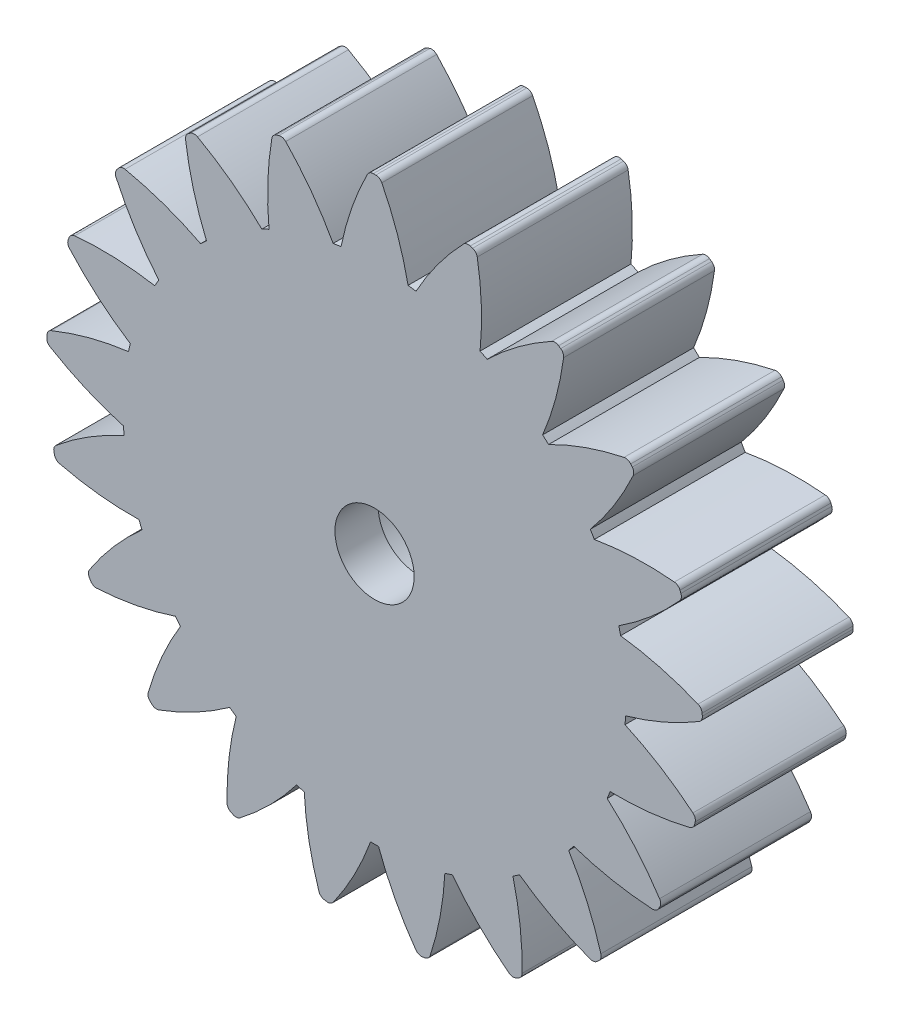
SolidWorks part; units mm, degrees
material "PET"
ref_plane "Front Plane" through (0, 0, 0) normal (0, 0, 1) x (1, 0, 0)
ref_plane "Top Plane" through (0, 0, 0) normal (0, 1, 0) x (1, 0, 0)
ref_plane "Right Plane" through (0, 0, 0) normal (1, 0, 0) x (0, 0, -1)
sketch "Sketch2" plane through (0, 0, 0) normal (0, 0, 1) x (1, 0, 0)
  circle A0 centre (0, 0) radius 9.525
  dimension "D1" = 19.05
extrude "Boss-Extrude1" add sketch "Sketch2" along normal blind 5.08 contours A0
sketch "Sketch3" plane through (0, 0, 5.08) normal (0, 0, 1) x (1, 0, 0)
  circle A0 centre (0, 0) radius 2.8956
  dimension "D1" = 5.7912
extrude "Cut-Extrude1" cut sketch "Sketch3" against normal up to surface (5.08 mm away) up to face at (9.525, 0, 0)
sketch "Sketch4" plane through (0, 0, 5.08) normal (0, 0, 1) x (1, 0, 0)
  line L0 (0, 0) -> (0, 15.3414) construction
  line L2 (-0.0481, 12.446) -> (0.0481, 12.446)
  arc A0 (0.2748, 12.3064) -> (0.0481, 12.446) centre (0.0481, 12.192) ccw
  arc A1 (-1.27, 9.44) -> (-0.2748, 12.3064) centre (9.9298, 7.1576) cw
  circle A2 centre (0, 0) radius 9.525 construction
  arc A3 (1.27, 9.44) -> (-1.27, 9.44) centre (0, 0) ccw
  arc A4 (1.27, 9.44) -> (0.2748, 12.3064) centre (-9.9298, 7.1576) ccw
  arc A5 (-0.2748, 12.3064) -> (-0.0481, 12.446) centre (-0.0481, 12.192) cw
  point P12 (0.2032, 12.446)
  point P14 (0, 12.446)
  point P16 (0, 9.525)
  point P19 (-0.2032, 12.446)
  dimension "D2" = 11.43
  dimension "D5" = 0.254
  dimension "D1" = 0.2032
  dimension "D3" = 2.921
  dimension "D4" = 1.27
extrude "Boss-Extrude2" add sketch "Sketch4" against normal up to surface (5.08 mm away) up to face at (2.8956, 0, 0)
pattern_circular "CirPattern1" count 21 over 360 about axis through (0, 0, 0) along (0, 0, 1) of "Boss-Extrude2"
sketch "Sketch5" plane through (0, 0, 5.08) normal (0, 0, 1) x (1, 0, 0)
  line L27 (-3.6226, 11.9072) -> (-3.7145, 11.8789)
  line L28 (-6.9714, 10.3104) -> (-7.0508, 10.2563)
  line L29 (-9.7007, 7.7975) -> (-9.7606, 7.7224)
  line L30 (-11.5681, 4.5918) -> (-11.6032, 4.5023)
  line L31 (-12.4076, 0.978) -> (-12.4148, 0.8822)
  line L32 (-12.1446, -2.7226) -> (-12.1233, -2.8164)
  line L33 (-10.8026, -6.1814) -> (-10.7545, -6.2646)
  line L34 (-8.5007, -9.0909) -> (-8.4302, -9.1563)
  line L35 (-5.4434, -11.1926) -> (-5.3568, -11.2343)
  line L36 (-1.9025, -12.2998) -> (-1.8075, -12.3142)
  line L37 (1.8075, -12.3142) -> (1.9025, -12.2998)
  line L38 (5.3568, -11.2343) -> (5.4434, -11.1926)
  line L39 (8.4302, -9.1563) -> (8.5007, -9.0909)
  line L40 (10.7545, -6.2646) -> (10.8026, -6.1814)
  line L41 (12.1233, -2.8164) -> (12.1446, -2.7226)
  line L42 (12.4148, 0.8822) -> (12.4076, 0.978)
  line L43 (11.6032, 4.5023) -> (11.5681, 4.5918)
  line L44 (9.7606, 7.7224) -> (9.7007, 7.7975)
  line L45 (7.0508, 10.2563) -> (6.9714, 10.3104)
  line L46 (3.7145, 11.8789) -> (3.6226, 11.9072)
  line L53 (0.0481, 12.446) -> (-0.0481, 12.446)
  line L54 (-3.6226, 11.9072) -> (-3.7145, 11.8789)
  line L55 (-6.9714, 10.3104) -> (-7.0508, 10.2563)
  line L56 (-9.7007, 7.7975) -> (-9.7606, 7.7224)
  line L57 (-11.5681, 4.5918) -> (-11.6032, 4.5023)
  line L58 (-12.4076, 0.978) -> (-12.4148, 0.8822)
  line L59 (-12.1446, -2.7226) -> (-12.1233, -2.8164)
  line L60 (-10.8026, -6.1814) -> (-10.7545, -6.2646)
  line L61 (-8.5007, -9.0909) -> (-8.4302, -9.1563)
  line L62 (-5.4434, -11.1926) -> (-5.3568, -11.2343)
  line L63 (-1.9025, -12.2998) -> (-1.8075, -12.3142)
  line L64 (1.8075, -12.3142) -> (1.9025, -12.2998)
  line L65 (5.3568, -11.2343) -> (5.4434, -11.1926)
  line L66 (8.4302, -9.1563) -> (8.5007, -9.0909)
  line L67 (10.7545, -6.2646) -> (10.8026, -6.1814)
  line L68 (12.1233, -2.8164) -> (12.1446, -2.7226)
  line L69 (12.4148, 0.8822) -> (12.4076, 0.978)
  line L70 (11.6032, 4.5023) -> (11.5681, 4.5918)
  line L71 (9.7606, 7.7224) -> (9.7007, 7.7975)
  line L72 (7.0508, 10.2563) -> (6.9714, 10.3104)
  line L73 (3.7145, 11.8789) -> (3.6226, 11.9072)
  line L80 (0.0481, 12.446) -> (-0.0481, 12.446)
  circle A0 centre (0, 0) radius 1.5
  arc A64 (-1.27, 9.44) -> (-1.5689, 9.3949) centre (0, 0) ccw
  arc A65 (-1.27, 9.44) -> (-1.5689, 9.3949) centre (0, 0) ccw
  arc A66 (-3.9961, 8.6462) -> (-4.2684, 8.5151) centre (0, 0) ccw
  arc A67 (-3.9961, 8.6462) -> (-4.2684, 8.5151) centre (0, 0) ccw
  arc A68 (-6.367, 7.0842) -> (-6.5886, 6.8786) centre (0, 0) ccw
  arc A69 (-6.367, 7.0842) -> (-6.5886, 6.8786) centre (0, 0) ccw
  arc A70 (-8.1723, 4.8928) -> (-8.3234, 4.631) centre (0, 0) ccw
  arc A71 (-8.1723, 4.8928) -> (-8.3234, 4.631) centre (0, 0) ccw
  arc A72 (-9.2514, 2.2666) -> (-9.3187, 1.9719) centre (0, 0) ccw
  arc A73 (-9.2514, 2.2666) -> (-9.3187, 1.9719) centre (0, 0) ccw
  arc A74 (-9.5085, -0.561) -> (-9.4859, -0.8624) centre (0, 0) ccw
  arc A75 (-9.5085, -0.561) -> (-9.4859, -0.8624) centre (0, 0) ccw
  arc A76 (-8.9207, -3.3387) -> (-8.8102, -3.6201) centre (0, 0) ccw
  arc A77 (-8.9207, -3.3387) -> (-8.8102, -3.6201) centre (0, 0) ccw
  arc A78 (-7.5402, -5.8198) -> (-7.3518, -6.0562) centre (0, 0) ccw
  arc A79 (-7.5402, -5.8198) -> (-7.3518, -6.0562) centre (0, 0) ccw
  arc A80 (-5.4898, -7.7838) -> (-5.2401, -7.9541) centre (0, 0) ccw
  arc A81 (-5.4898, -7.7838) -> (-5.2401, -7.9541) centre (0, 0) ccw
  arc A82 (-2.9516, -9.0561) -> (-2.6628, -9.1452) centre (0, 0) ccw
  arc A83 (-1.5689, 9.3949) -> (-3.3648, 11.8407) centre (-11.5984, 3.9128) ccw
  arc A84 (-3.89, 11.6787) -> (-3.9961, 8.6462) centre (7.3789, 9.7665) ccw
  arc A85 (-2.9516, -9.0561) -> (-2.6628, -9.1452) centre (0, 0) ccw
  arc A86 (-4.2684, 8.5151) -> (-6.7054, 10.3229) centre (-12.2364, 0.3202) ccw
  arc A87 (-7.1595, 10.0132) -> (-6.367, 7.0842) centre (4.1724, 11.5076) ccw
  arc A88 (-0.1511, -9.5238) -> (0.1511, -9.5238) centre (0, 0) ccw
  arc A89 (-6.5886, 6.8786) -> (-9.4502, 7.8878) centre (-11.7872, -3.3007) ccw
  arc A90 (-9.7929, 7.4581) -> (-8.1723, 4.8928) centre (0.5951, 12.2262) ccw
  arc A91 (-0.1511, -9.5238) -> (0.1511, -9.5238) centre (0, 0) ccw
  arc A92 (-8.3234, 4.631) -> (-11.3553, 4.7519) centre (-10.2906, -6.6284) ccw
  arc A93 (-11.5561, 4.2402) -> (-9.2514, 2.2666) centre (-3.0351, 11.8584) ccw
  arc A94 (2.6628, -9.1452) -> (2.9516, -9.0561) centre (0, 0) ccw
  arc A95 (-9.3187, 1.9719) -> (-12.2515, 1.1937) centre (-7.8797, -9.3672) ccw
  arc A96 (-12.2925, 0.6456) -> (-9.5085, -0.561) centre (-6.3956, 10.4369) ccw
  arc A97 (2.6628, -9.1452) -> (2.9516, -9.0561) centre (0, 0) ccw
  arc A98 (-9.4859, -0.8624) -> (-12.059, -2.4705) centre (-4.7686, -11.2736) ccw
  arc A99 (-11.9367, -3.0064) -> (-8.9207, -3.3387) centre (-9.1878, 8.0881) ccw
  arc A100 (5.2401, -7.9541) -> (5.4898, -7.7838) centre (0, 0) ccw
  arc A101 (-8.8102, -3.6201) -> (-10.7951, -5.9152) centre (-1.2338, -12.1783) ccw
  arc A102 (-10.5203, -6.3912) -> (-7.5402, -5.8198) centre (-11.1636, 5.0207) ccw
  arc A103 (5.2401, -7.9541) -> (5.4898, -7.7838) centre (0, 0) ccw
  arc A104 (-7.3518, -6.0562) -> (-8.572, -8.8343) centre (2.4106, -12.0009) ccw
  arc A105 (-8.169, -9.2082) -> (-5.4898, -7.7838) centre (-12.1475, 1.5071) ccw
  arc A106 (7.3518, -6.0562) -> (7.5402, -5.8198) centre (0, 0) ccw
  arc A107 (-5.2401, -7.9541) -> (-5.5872, -10.9685) centre (5.8409, -10.7572) ccw
  arc A108 (-5.0919, -11.2069) -> (-2.9516, -9.0561) centre (-12.052, -2.1404) ccw
  arc A109 (7.3518, -6.0562) -> (7.5402, -5.8198) centre (0, 0) ccw
  arc A110 (-2.6628, -9.1452) -> (-2.1059, -12.128) centre (8.7521, -8.5576) ccw
  arc A111 (-1.5624, -12.2099) -> (-0.1511, -9.5238) centre (-10.8857, -5.5977) ccw
  arc A112 (8.8102, -3.6201) -> (8.9207, -3.3387) centre (0, 0) ccw
  arc A113 (0.1511, -9.5238) -> (1.5624, -12.2099) centre (10.8857, -5.5977) ccw
  arc A114 (2.1059, -12.128) -> (2.6628, -9.1452) centre (-8.7521, -8.5576) ccw
  arc A115 (8.8102, -3.6201) -> (8.9207, -3.3387) centre (0, 0) ccw
  arc A116 (2.9516, -9.0561) -> (5.0919, -11.2069) centre (12.052, -2.1404) ccw
  arc A117 (5.5872, -10.9685) -> (5.2401, -7.9541) centre (-5.8409, -10.7572) ccw
  arc A118 (9.4859, -0.8624) -> (9.5085, -0.561) centre (0, 0) ccw
  arc A119 (5.4898, -7.7838) -> (8.169, -9.2082) centre (12.1475, 1.5071) ccw
  arc A120 (8.572, -8.8343) -> (7.3518, -6.0562) centre (-2.4106, -12.0009) ccw
  arc A121 (9.4859, -0.8624) -> (9.5085, -0.561) centre (0, 0) ccw
  arc A122 (7.5402, -5.8198) -> (10.5203, -6.3912) centre (11.1636, 5.0207) ccw
  arc A123 (10.7951, -5.9152) -> (8.8102, -3.6201) centre (1.2338, -12.1783) ccw
  arc A124 (9.3187, 1.9719) -> (9.2514, 2.2666) centre (0, 0) ccw
  arc A125 (8.9207, -3.3387) -> (11.9367, -3.0064) centre (9.1878, 8.0881) ccw
  arc A126 (12.059, -2.4705) -> (9.4859, -0.8624) centre (4.7686, -11.2736) ccw
  arc A127 (9.3187, 1.9719) -> (9.2514, 2.2666) centre (0, 0) ccw
  arc A128 (9.5085, -0.561) -> (12.2925, 0.6456) centre (6.3956, 10.4369) ccw
  arc A129 (12.2515, 1.1937) -> (9.3187, 1.9719) centre (7.8797, -9.3672) ccw
  arc A130 (8.3234, 4.631) -> (8.1723, 4.8928) centre (0, 0) ccw
  arc A131 (9.2514, 2.2666) -> (11.5561, 4.2402) centre (3.0351, 11.8584) ccw
  arc A132 (11.3553, 4.7519) -> (8.3234, 4.631) centre (10.2906, -6.6284) ccw
  arc A133 (8.3234, 4.631) -> (8.1723, 4.8928) centre (0, 0) ccw
  arc A134 (8.1723, 4.8928) -> (9.7929, 7.4581) centre (-0.5951, 12.2262) ccw
  arc A135 (9.4502, 7.8878) -> (6.5886, 6.8786) centre (11.7872, -3.3007) ccw
  arc A136 (6.5886, 6.8786) -> (6.367, 7.0842) centre (0, 0) ccw
  arc A137 (6.367, 7.0842) -> (7.1595, 10.0132) centre (-4.1724, 11.5076) ccw
  arc A138 (6.7054, 10.3229) -> (4.2684, 8.5151) centre (12.2364, 0.3202) ccw
  arc A139 (6.5886, 6.8786) -> (6.367, 7.0842) centre (0, 0) ccw
  arc A140 (3.9961, 8.6462) -> (3.89, 11.6787) centre (-7.3789, 9.7665) ccw
  arc A141 (3.3648, 11.8407) -> (1.5689, 9.3949) centre (11.5984, 3.9128) ccw
  arc A142 (4.2684, 8.5151) -> (3.9961, 8.6462) centre (0, 0) ccw
  arc A143 (4.2684, 8.5151) -> (3.9961, 8.6462) centre (0, 0) ccw
  arc A144 (1.5689, 9.3949) -> (1.27, 9.44) centre (0, 0) ccw
  arc A145 (1.5689, 9.3949) -> (1.27, 9.44) centre (0, 0) ccw
  arc A161 (1.27, 9.44) -> (0.2748, 12.3064) centre (-9.9298, 7.1576) ccw
  arc A162 (-0.2748, 12.3064) -> (-1.27, 9.44) centre (9.9298, 7.1576) ccw
  arc A164 (-1.5689, 9.3949) -> (-3.3648, 11.8407) centre (-11.5984, 3.9128) ccw
  arc A165 (-3.89, 11.6787) -> (-3.9961, 8.6462) centre (7.3789, 9.7665) ccw
  arc A167 (-4.2684, 8.5151) -> (-6.7054, 10.3229) centre (-12.2364, 0.3202) ccw
  arc A168 (-7.1595, 10.0132) -> (-6.367, 7.0842) centre (4.1724, 11.5076) ccw
  arc A170 (-6.5886, 6.8786) -> (-9.4502, 7.8878) centre (-11.7872, -3.3007) ccw
  arc A171 (-9.7929, 7.4581) -> (-8.1723, 4.8928) centre (0.5951, 12.2262) ccw
  arc A173 (-8.3234, 4.631) -> (-11.3553, 4.7519) centre (-10.2906, -6.6284) ccw
  arc A174 (-11.5561, 4.2402) -> (-9.2514, 2.2666) centre (-3.0351, 11.8584) ccw
  arc A176 (-9.3187, 1.9719) -> (-12.2515, 1.1937) centre (-7.8797, -9.3672) ccw
  arc A177 (-12.2925, 0.6456) -> (-9.5085, -0.561) centre (-6.3956, 10.4369) ccw
  arc A179 (-9.4859, -0.8624) -> (-12.059, -2.4705) centre (-4.7686, -11.2736) ccw
  arc A180 (-11.9367, -3.0064) -> (-8.9207, -3.3387) centre (-9.1878, 8.0881) ccw
  arc A182 (-8.8102, -3.6201) -> (-10.7951, -5.9152) centre (-1.2338, -12.1783) ccw
  arc A183 (-10.5203, -6.3912) -> (-7.5402, -5.8198) centre (-11.1636, 5.0207) ccw
  arc A185 (-7.3518, -6.0562) -> (-8.572, -8.8343) centre (2.4106, -12.0009) ccw
  arc A186 (-8.169, -9.2082) -> (-5.4898, -7.7838) centre (-12.1475, 1.5071) ccw
  arc A188 (-5.2401, -7.9541) -> (-5.5872, -10.9685) centre (5.8409, -10.7572) ccw
  arc A189 (-5.0919, -11.2069) -> (-2.9516, -9.0561) centre (-12.052, -2.1404) ccw
  arc A191 (-2.6628, -9.1452) -> (-2.1059, -12.128) centre (8.7521, -8.5576) ccw
  arc A192 (-1.5624, -12.2099) -> (-0.1511, -9.5238) centre (-10.8857, -5.5977) ccw
  arc A194 (0.1511, -9.5238) -> (1.5624, -12.2099) centre (10.8857, -5.5977) ccw
  arc A195 (2.1059, -12.128) -> (2.6628, -9.1452) centre (-8.7521, -8.5576) ccw
  arc A197 (2.9516, -9.0561) -> (5.0919, -11.2069) centre (12.052, -2.1404) ccw
  arc A198 (5.5872, -10.9685) -> (5.2401, -7.9541) centre (-5.8409, -10.7572) ccw
  arc A200 (5.4898, -7.7838) -> (8.169, -9.2082) centre (12.1475, 1.5071) ccw
  arc A201 (8.572, -8.8343) -> (7.3518, -6.0562) centre (-2.4106, -12.0009) ccw
  arc A203 (7.5402, -5.8198) -> (10.5203, -6.3912) centre (11.1636, 5.0207) ccw
  arc A204 (10.7951, -5.9152) -> (8.8102, -3.6201) centre (1.2338, -12.1783) ccw
  arc A206 (8.9207, -3.3387) -> (11.9367, -3.0064) centre (9.1878, 8.0881) ccw
  arc A207 (12.059, -2.4705) -> (9.4859, -0.8624) centre (4.7686, -11.2736) ccw
  arc A209 (9.5085, -0.561) -> (12.2925, 0.6456) centre (6.3956, 10.4369) ccw
  arc A210 (12.2515, 1.1937) -> (9.3187, 1.9719) centre (7.8797, -9.3672) ccw
  arc A212 (9.2514, 2.2666) -> (11.5561, 4.2402) centre (3.0351, 11.8584) ccw
  arc A213 (11.3553, 4.7519) -> (8.3234, 4.631) centre (10.2906, -6.6284) ccw
  arc A215 (8.1723, 4.8928) -> (9.7929, 7.4581) centre (-0.5951, 12.2262) ccw
  arc A216 (9.4502, 7.8878) -> (6.5886, 6.8786) centre (11.7872, -3.3007) ccw
  arc A218 (6.367, 7.0842) -> (7.1595, 10.0132) centre (-4.1724, 11.5076) ccw
  arc A219 (6.7054, 10.3229) -> (4.2684, 8.5151) centre (12.2364, 0.3202) ccw
  arc A221 (3.9961, 8.6462) -> (3.89, 11.6787) centre (-7.3789, 9.7665) ccw
  arc A222 (3.3648, 11.8407) -> (1.5689, 9.3949) centre (11.5984, 3.9128) ccw
  arc A242 (1.27, 9.44) -> (0.2748, 12.3064) centre (-9.9298, 7.1576) ccw
  arc A243 (-0.2748, 12.3064) -> (-1.27, 9.44) centre (9.9298, 7.1576) ccw
  arc A283 (-3.3648, 11.8407) -> (-3.6226, 11.9072) centre (-3.5477, 11.6645) ccw
  arc A285 (-3.3648, 11.8407) -> (-3.6226, 11.9072) centre (-3.5477, 11.6645) ccw
  arc A287 (-3.7145, 11.8789) -> (-3.89, 11.6787) centre (-3.6396, 11.6362) ccw
  arc A289 (-3.7145, 11.8789) -> (-3.89, 11.6787) centre (-3.6396, 11.6362) ccw
  arc A291 (-6.7054, 10.3229) -> (-6.9714, 10.3104) centre (-6.8283, 10.1006) ccw
  arc A293 (-6.7054, 10.3229) -> (-6.9714, 10.3104) centre (-6.8283, 10.1006) ccw
  arc A295 (-7.0508, 10.2563) -> (-7.1595, 10.0132) centre (-6.9077, 10.0464) ccw
  arc A297 (-7.0508, 10.2563) -> (-7.1595, 10.0132) centre (-6.9077, 10.0464) ccw
  arc A299 (-9.4502, 7.8878) -> (-9.7007, 7.7975) centre (-9.5021, 7.6392) ccw
  arc A301 (-9.4502, 7.8878) -> (-9.7007, 7.7975) centre (-9.5021, 7.6392) ccw
  arc A303 (-9.7606, 7.7224) -> (-9.7929, 7.4581) centre (-9.5621, 7.564) ccw
  arc A305 (-9.7606, 7.7224) -> (-9.7929, 7.4581) centre (-9.5621, 7.564) ccw
  arc A307 (-11.3553, 4.7519) -> (-11.5681, 4.5918) centre (-11.3317, 4.499) ccw
  arc A308 (-11.3553, 4.7519) -> (-11.5681, 4.5918) centre (-11.3317, 4.499) ccw
  arc A309 (-11.6032, 4.5023) -> (-11.5561, 4.2402) centre (-11.3668, 4.4095) ccw
  arc A310 (-11.6032, 4.5023) -> (-11.5561, 4.2402) centre (-11.3668, 4.4095) ccw
  arc A311 (-12.2515, 1.1937) -> (-12.4076, 0.978) centre (-12.1543, 0.959) ccw
  arc A312 (-12.2515, 1.1937) -> (-12.4076, 0.978) centre (-12.1543, 0.959) ccw
  arc A313 (-12.4148, 0.8822) -> (-12.2925, 0.6456) centre (-12.1615, 0.8632) ccw
  arc A314 (-12.4148, 0.8822) -> (-12.2925, 0.6456) centre (-12.1615, 0.8632) ccw
  arc A315 (-12.059, -2.4705) -> (-12.1446, -2.7226) centre (-11.897, -2.6661) ccw
  arc A316 (-12.059, -2.4705) -> (-12.1446, -2.7226) centre (-11.897, -2.6661) ccw
  arc A318 (-12.1233, -2.8164) -> (-11.9367, -3.0064) centre (-11.8756, -2.7598) ccw
  arc A320 (-12.1233, -2.8164) -> (-11.9367, -3.0064) centre (-11.8756, -2.7598) ccw
  arc A322 (-10.7951, -5.9152) -> (-10.8026, -6.1814) centre (-10.5826, -6.0544) ccw
  arc A324 (-10.7951, -5.9152) -> (-10.8026, -6.1814) centre (-10.5826, -6.0544) ccw
  arc A326 (-10.7545, -6.2646) -> (-10.5203, -6.3912) centre (-10.5346, -6.1376) ccw
  arc A328 (-10.7545, -6.2646) -> (-10.5203, -6.3912) centre (-10.5346, -6.1376) ccw
  arc A329 (-8.572, -8.8343) -> (-8.5007, -9.0909) centre (-8.3279, -8.9047) ccw
  arc A330 (-8.572, -8.8343) -> (-8.5007, -9.0909) centre (-8.3279, -8.9047) ccw
  arc A331 (-8.4302, -9.1563) -> (-8.169, -9.2082) centre (-8.2574, -8.9701) ccw
  arc A332 (-8.4302, -9.1563) -> (-8.169, -9.2082) centre (-8.2574, -8.9701) ccw
  arc A333 (-5.5872, -10.9685) -> (-5.4434, -11.1926) centre (-5.3332, -10.9638) ccw
  arc A334 (-5.5872, -10.9685) -> (-5.4434, -11.1926) centre (-5.3332, -10.9638) ccw
  arc A335 (-5.3568, -11.2343) -> (-5.0919, -11.2069) centre (-5.2466, -11.0055) ccw
  arc A336 (-5.3568, -11.2343) -> (-5.0919, -11.2069) centre (-5.2466, -11.0055) ccw
  arc A337 (-2.1059, -12.128) -> (-1.9025, -12.2998) centre (-1.8646, -12.0487) ccw
  arc A338 (-2.1059, -12.128) -> (-1.9025, -12.2998) centre (-1.8646, -12.0487) ccw
  arc A339 (-1.8075, -12.3142) -> (-1.5624, -12.2099) centre (-1.7696, -12.063) ccw
  arc A340 (-1.8075, -12.3142) -> (-1.5624, -12.2099) centre (-1.7696, -12.063) ccw
  arc A341 (1.5624, -12.2099) -> (1.8075, -12.3142) centre (1.7696, -12.063) ccw
  arc A342 (1.5624, -12.2099) -> (1.8075, -12.3142) centre (1.7696, -12.063) ccw
  arc A343 (1.9025, -12.2998) -> (2.1059, -12.128) centre (1.8646, -12.0487) ccw
  arc A344 (1.9025, -12.2998) -> (2.1059, -12.128) centre (1.8646, -12.0487) ccw
  arc A345 (5.0919, -11.2069) -> (5.3568, -11.2343) centre (5.2466, -11.0055) ccw
  arc A346 (5.0919, -11.2069) -> (5.3568, -11.2343) centre (5.2466, -11.0055) ccw
  arc A347 (5.4434, -11.1926) -> (5.5872, -10.9685) centre (5.3332, -10.9638) ccw
  arc A348 (5.4434, -11.1926) -> (5.5872, -10.9685) centre (5.3332, -10.9638) ccw
  arc A349 (8.169, -9.2082) -> (8.4302, -9.1563) centre (8.2574, -8.9701) ccw
  arc A350 (8.169, -9.2082) -> (8.4302, -9.1563) centre (8.2574, -8.9701) ccw
  arc A351 (8.5007, -9.0909) -> (8.572, -8.8343) centre (8.3279, -8.9047) ccw
  arc A352 (8.5007, -9.0909) -> (8.572, -8.8343) centre (8.3279, -8.9047) ccw
  arc A353 (10.5203, -6.3912) -> (10.7545, -6.2646) centre (10.5346, -6.1376) ccw
  arc A354 (10.5203, -6.3912) -> (10.7545, -6.2646) centre (10.5346, -6.1376) ccw
  arc A355 (10.8026, -6.1814) -> (10.7951, -5.9152) centre (10.5826, -6.0544) ccw
  arc A356 (10.8026, -6.1814) -> (10.7951, -5.9152) centre (10.5826, -6.0544) ccw
  arc A357 (11.9367, -3.0064) -> (12.1233, -2.8164) centre (11.8756, -2.7598) ccw
  arc A358 (11.9367, -3.0064) -> (12.1233, -2.8164) centre (11.8756, -2.7598) ccw
  arc A359 (12.1446, -2.7226) -> (12.059, -2.4705) centre (11.897, -2.6661) ccw
  arc A360 (12.1446, -2.7226) -> (12.059, -2.4705) centre (11.897, -2.6661) ccw
  arc A361 (12.2925, 0.6456) -> (12.4148, 0.8822) centre (12.1615, 0.8632) ccw
  arc A362 (12.2925, 0.6456) -> (12.4148, 0.8822) centre (12.1615, 0.8632) ccw
  arc A363 (12.4076, 0.978) -> (12.2515, 1.1937) centre (12.1543, 0.959) ccw
  arc A364 (12.4076, 0.978) -> (12.2515, 1.1937) centre (12.1543, 0.959) ccw
  arc A365 (11.5561, 4.2402) -> (11.6032, 4.5023) centre (11.3668, 4.4095) ccw
  arc A366 (11.5561, 4.2402) -> (11.6032, 4.5023) centre (11.3668, 4.4095) ccw
  arc A367 (11.5681, 4.5918) -> (11.3553, 4.7519) centre (11.3317, 4.499) ccw
  arc A368 (11.5681, 4.5918) -> (11.3553, 4.7519) centre (11.3317, 4.499) ccw
  arc A369 (9.7929, 7.4581) -> (9.7606, 7.7224) centre (9.5621, 7.564) ccw
  arc A370 (9.7929, 7.4581) -> (9.7606, 7.7224) centre (9.5621, 7.564) ccw
  arc A371 (9.7007, 7.7975) -> (9.4502, 7.8878) centre (9.5021, 7.6392) ccw
  arc A372 (9.7007, 7.7975) -> (9.4502, 7.8878) centre (9.5021, 7.6392) ccw
  arc A373 (7.1595, 10.0132) -> (7.0508, 10.2563) centre (6.9077, 10.0464) ccw
  arc A374 (7.1595, 10.0132) -> (7.0508, 10.2563) centre (6.9077, 10.0464) ccw
  arc A375 (6.9714, 10.3104) -> (6.7054, 10.3229) centre (6.8283, 10.1006) ccw
  arc A376 (6.9714, 10.3104) -> (6.7054, 10.3229) centre (6.8283, 10.1006) ccw
  arc A377 (3.89, 11.6787) -> (3.7145, 11.8789) centre (3.6396, 11.6362) ccw
  arc A378 (3.89, 11.6787) -> (3.7145, 11.8789) centre (3.6396, 11.6362) ccw
  arc A379 (3.6226, 11.9072) -> (3.3648, 11.8407) centre (3.5477, 11.6645) ccw
  arc A380 (3.6226, 11.9072) -> (3.3648, 11.8407) centre (3.5477, 11.6645) ccw
  arc A381 (0.2748, 12.3064) -> (0.0481, 12.446) centre (0.0481, 12.192) ccw
  arc A382 (0.2748, 12.3064) -> (0.0481, 12.446) centre (0.0481, 12.192) ccw
  arc A383 (-0.0481, 12.446) -> (-0.2748, 12.3064) centre (-0.0481, 12.192) ccw
  arc A384 (-0.0481, 12.446) -> (-0.2748, 12.3064) centre (-0.0481, 12.192) ccw
  dimension "D1" = 3
  dimension "D2" = 0
extrude "Boss-Extrude3" add sketch "Sketch5" along normal blind 0.635
sketch "Sketch6" plane through (0, 0, 5.08) normal (0, 0, -1) x (-1, 0, 0)
  circle A0 centre (0, 0) radius 1.5 construction
  circle A1 centre (0, 0) radius 2.8956
  circle A2 centre (0, 0) radius 2.8956
  circle A3 centre (0, 0) radius 1.5
  dimension "D1" = 0
extrude "Boss-Extrude4" add sketch "Sketch6" along normal blind 1
ref_plane "Plane1" through (0, 0, 2.8575) normal (0, 0, -1) x (-1, 0, 0)
